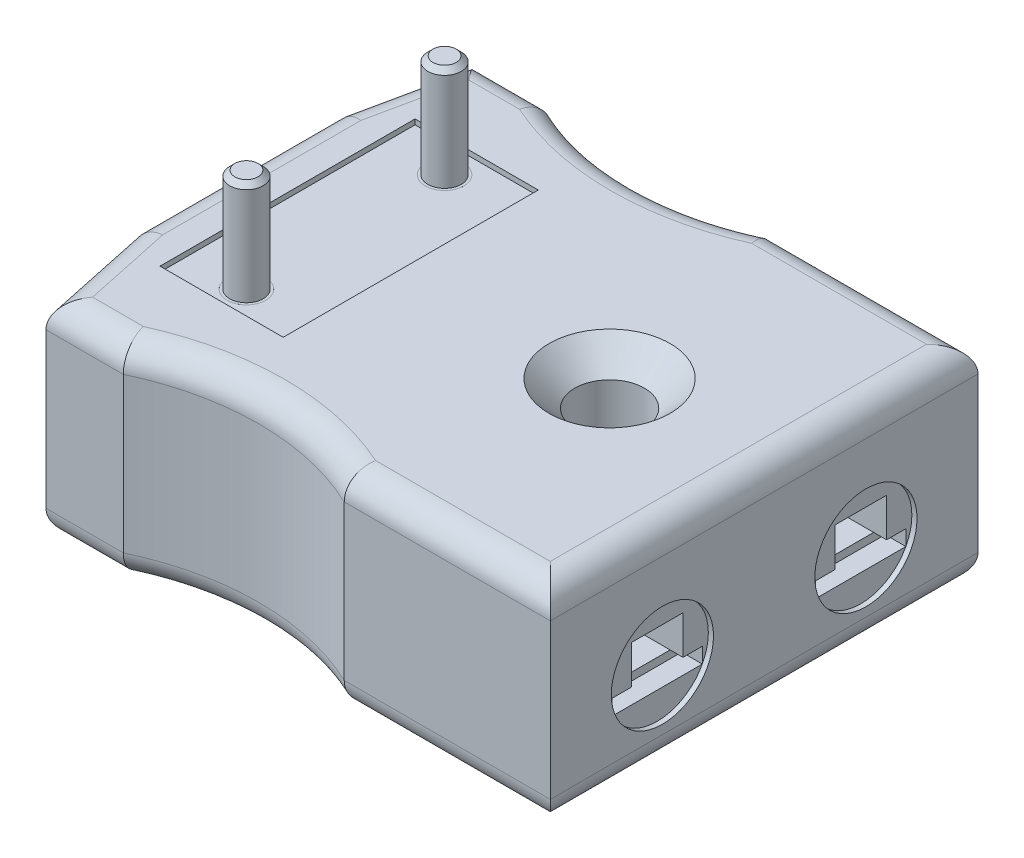
SolidWorks part; units mm, degrees
ref_plane "Front Plane" through (0, 0, 0) normal (0, 0, 1) x (1, 0, 0)
ref_plane "Top Plane" through (0, 0, 0) normal (0, 1, 0) x (1, 0, 0)
ref_plane "Right Plane" through (0, 0, 0) normal (1, 0, 0) x (0, 0, -1)
sketch "Sketch1" plane through (0, 0, 0) normal (0, 1, 0) x (1, 0, 0)
  line L0 (0, -3.95) -> (0, 3.95)
  line L1 (0, 0) -> (28.7651, 0) construction
  line L2 (0, 3.95) -> (0.9246, 8.3)
  line L3 (0.9246, 8.3) -> (3.9246, 8.3)
  line L4 (12.5, 8.3) -> (20.5, 8.3)
  line L5 (20.5, 8.3) -> (20.5, -8.3)
  line L6 (12.5, -8.3) -> (20.5, -8.3)
  line L7 (0.9246, -8.3) -> (3.9246, -8.3)
  line L8 (0, -3.95) -> (0.9246, -8.3)
  arc A0 (3.9246, 8.3) -> (12.5, 8.3) centre (8.2123, 17.3341) ccw
  arc A1 (3.9246, -8.3) -> (12.5, -8.3) centre (8.2123, -17.3341) cw
  point P4 (0, 0)
  point P13 (20.5, 0)
  dimension "D4" = 10
  dimension "D1" = 7.9
  dimension "D2" = 20.5
  dimension "D3" = 16.6
  dimension "D5" = 8
  dimension "D6" = 102
  dimension "D7" = 3
extrude "Boss-Extrude1" add sketch "Sketch1" along normal blind 8
fillet "Fillet1" radius 1 20 edges at (0, 0, 0) (0.4623, 0, 6.125) (2.4246, 0, 8.3) (8.2123, 0, 7.3341) (16.5, 0, 8.3) (20.5, 0, 0) (16.5, 0, -8.3) (8.2123, 0, -7.3341) (2.4246, 0, -8.3) (0.4623, 0, -6.125) (2.4246, 8, -8.3) (8.2123, 8, -7.3341) (16.5, 8, -8.3) (20.5, 8, 0) (16.5, 8, 8.3) (8.2123, 8, 7.3341) (2.4246, 8, 8.3) (0.4623, 8, 6.125) (0, 8, 0) (0.4623, 8, -6.125)
sketch "Sketch2" plane through (0, 8, 0) normal (0, 1, 0) x (1, 0, 0)
  line L0 (20.5, 8.3) -> (20.5, -8.3) construction
  circle A1 centre (14.5, 0) radius 1.35
  dimension "D2" = 2.7
  dimension "D1" = 6
extrude "Cut-Extrude1" cut sketch "Sketch2" against normal through all
chamfer "Chamfer1" distance 1 angle 45 2 edges at (14.5, 0, 1.35) (14.5, 8, 1.35)
sketch "Sketch3" plane through (20.5, 0, 0) normal (-1, 0, 0) x (0, 0, 1)
  line L0 (-4.95, 4.5) -> (-2.95, 4.5)
  line L1 (-2.95, 4.5) -> (-2.95, 3)
  line L2 (-2.95, 3) -> (-2.2, 3)
  line L3 (-2.2, 3) -> (-2.2, 2.4)
  line L4 (-2.2, 2.4) -> (-5.7, 2.4)
  line L5 (-5.7, 2.4) -> (-5.7, 3)
  line L6 (-5.7, 3) -> (-4.95, 3)
  line L7 (-4.95, 3) -> (-4.95, 4.5)
  line L8 (0, 0) -> (0, 9.9505) construction
  line L9 (-3.95, 7) -> (-3.95, 1) construction
  line L10 (3.95, 7) -> (-3.95, 7) construction
  line L11 (4.95, 3) -> (4.95, 4.5)
  line L12 (5.7, 3) -> (4.95, 3)
  line L13 (5.7, 2.4) -> (5.7, 3)
  line L14 (2.2, 2.4) -> (5.7, 2.4)
  line L15 (2.2, 3) -> (2.2, 2.4)
  line L16 (2.95, 3) -> (2.2, 3)
  line L17 (2.95, 4.5) -> (2.95, 3)
  line L18 (4.95, 4.5) -> (2.95, 4.5)
  point P11 (-3.95, 4.5)
  dimension "D1" = 2
  dimension "D2" = 1.5
  dimension "D3" = 0.6
  dimension "D4" = 2.5
  dimension "D5" = 3.5
extrude "Cut-Extrude2" cut sketch "Sketch3" along normal blind 5
sketch "Sketch4" plane through (15.5, 0, 0) normal (1, 0, 0) x (0, 0, -1)
  line L1 (-2.2, 3) -> (-2.2, 2.4) construction
  line L2 (-5.7, 2.4) -> (-2.2, 2.4)
  line L3 (-5.7, 2.4) -> (-5.7, 2.7)
  line L4 (-5.7, 2.7) -> (-2.2, 2.7)
  line L6 (-2.2, 2.4) -> (-2.2, 2.7)
  line L7 (5.7, 3) -> (5.7, 2.4) construction
  line L8 (2.2, 2.4) -> (5.7, 2.4)
  line L9 (2.2, 2.4) -> (2.2, 2.7)
  line L10 (2.2, 2.7) -> (5.7, 2.7)
  line L11 (5.7, 2.4) -> (5.7, 2.7)
extrude "Boss-Extrude2" add sketch "Sketch4" along normal blind 4 separate body
sketch "Sketch5" plane through (0, 0, 0) normal (0, -1, 0) x (1, 0, 0)
  line L0 (0, 0) -> (5.599, 0) construction
  line L1 (2.75, 5.3449) -> (5.75, 5.3449)
  line L2 (2.75, 5.3449) -> (2.75, 4.5949)
  line L3 (2.75, 2.3449) -> (5.75, 2.3449)
  line L4 (5.75, 5.3449) -> (5.75, 2.3449)
  line L5 (2.75, 5.3449) -> (5.75, 2.3449) construction
  line L6 (2.75, 2.3449) -> (5.75, 5.3449) construction
  line L7 (-1.4662, -4.5949) -> (2.75, -4.5949)
  line L8 (2.75, -4.5949) -> (2.75, -5.3449)
  line L9 (2.75, 4.5949) -> (-1.4662, 4.5949)
  line L10 (2.75, -2.3449) -> (5.75, -5.3449) construction
  line L11 (2.75, -5.3449) -> (5.75, -2.3449) construction
  line L12 (5.75, -5.3449) -> (5.75, -2.3449)
  line L13 (2.75, -2.3449) -> (5.75, -2.3449)
  line L14 (2.75, -5.3449) -> (5.75, -5.3449)
  line L15 (20.5, 8.3) -> (20.5, -8.3) construction
  line L16 (-1.4662, 4.5949) -> (-1.4662, 3.0949)
  line L17 (-1.4662, 3.0949) -> (2.75, 3.0949)
  line L18 (2.75, 3.0949) -> (2.75, 2.3449)
  line L20 (-1.4662, -4.5949) -> (-1.4662, -3.0949)
  line L21 (-1.4662, -3.0949) -> (2.75, -3.0949)
  line L22 (2.75, -3.0949) -> (2.75, -2.3449)
  point P0 (4.25, 3.8449)
  point P17 (4.25, -3.8449)
  dimension "D1" = 3
  dimension "D2" = 16.25
  dimension "D3" = 1.5
  dimension "D4" = 3
extrude "Cut-Extrude3" cut sketch "Sketch5" against normal up to surface (2.4 mm away) up to face at (18, 2.4, 3.95)
sketch "Sketch6" plane through (0, 2.4, 0) normal (0, -1, 0) x (1, 0, 0)
  line L0 (2.75, 2.3449) -> (5.75, 2.3449) construction
  line L1 (5.75, 2.3449) -> (5.75, 5.3449) construction
  circle A0 centre (4.25, 3.8449) radius 1
  point P4 (4.25, 2.3449)
  point P7 (5.75, 3.8449)
extrude "Boss-Extrude3" add sketch "Sketch6" along normal blind 1.5 separate body
chamfer "Chamfer2" distance 0.2 angle 45 1 edges at (4.25, 0.9, 2.8449)
sketch "Sketch7" plane through (0, 0.9, 0) normal (0, -1, 0) x (1, 0, 0)
  line L1 (4.1, 3.0591) -> (4.4, 3.0591)
  line L2 (4.1, 3.0591) -> (4.1, 3.6949)
  line L3 (4.1, 4.6307) -> (4.4, 4.6307)
  line L4 (4.4, 3.0591) -> (4.4, 3.6949)
  line L7 (3.4642, 3.6949) -> (4.1, 3.6949)
  line L8 (3.4642, 3.6949) -> (3.4642, 3.9949)
  line L9 (3.4642, 3.9949) -> (4.1, 3.9949)
  line L10 (5.0358, 3.6949) -> (5.0358, 3.9949)
  line L13 (4.1, 3.9949) -> (4.1, 4.6307)
  line L16 (4.4, 3.6949) -> (5.0358, 3.6949)
  line L18 (4.4, 3.9949) -> (4.4, 4.6307)
  line L19 (4.4, 3.9949) -> (5.0358, 3.9949)
  line L20 (3.5028, 4.0095) -> (4.4, 4.6307) construction
  circle A0 centre (4.25, 3.8449) radius 0.8 construction
  point P0 (4.25, 3.8449)
  point P8 (3.5, 3.95)
  dimension "D1" = 0.3
extrude "Cut-Extrude4" cut sketch "Sketch7" against normal blind 1.5 draft 5
fillet "Fillet2" radius 0.2 4 edges at (4.3344, 1.65, 3.9293) (4.3344, 1.65, 3.7605) (4.1656, 1.65, 3.7605) (4.1656, 1.65, 3.9293)
mirror "Mirror1" about plane through (0, 0, 0) normal (0, 0, 1) of bodies 108
sketch "Sketch8" plane through (20.5, 0, 0) normal (-1, 0, 0) x (0, 0, 1)
  line L0 (0, 0) -> (0, 9.6072) construction
  circle A0 centre (3.95, 3.3335) radius 1.9834
  circle A1 centre (-3.95, 3.3335) radius 1.9834
extrude "Cut-Extrude5" cut sketch "Sketch8" along normal blind 0.2
sketch "Sketch9" plane through (0, 0, 0) normal (0, -1, 0) x (1, 0, 0)
  line L0 (19.5, 0) -> (7.4624, 0) construction
  line L1 (19.5, -7.3) -> (19.5, 7.3) construction
  circle A0 centre (17.5191, -3.95) radius 1.5
  circle A1 centre (17.5191, 3.95) radius 1.5
  dimension "D1" = 3
extrude "Cut-Extrude6" cut sketch "Sketch9" against normal blind 0.3
sketch "Sketch10" plane through (0, 0.3, 0) normal (0, -1, 0) x (1, 0, 0)
  line L0 (17.3546, 3.8537) -> (15.9216, 3.8537)
  line L1 (17.6546, 2.2868) -> (17.3546, 2.2868)
  line L2 (17.6546, 2.2868) -> (17.6546, 3.8537)
  line L3 (17.6546, 5.5955) -> (17.3546, 5.5955)
  line L4 (17.3546, 2.2868) -> (17.3546, 3.8537)
  line L5 (19.1575, 3.8537) -> (17.6546, 3.8537)
  line L6 (19.1575, 3.8537) -> (19.1575, 4.1537)
  line L7 (19.1575, 4.1537) -> (17.6546, 4.1537)
  line L8 (15.9216, 3.8537) -> (15.9216, 4.1537)
  line L9 (17.6546, 4.1537) -> (17.6546, 5.5955)
  line L10 (17.3546, 4.1537) -> (15.9216, 4.1537)
  line L11 (17.3546, 4.1537) -> (17.3546, 5.5955)
  dimension "D1" = 0.3
extrude "Boss-Extrude5" add sketch "Sketch10" along normal blind 0.3
sketch "Sketch11" plane through (0, 8, 0) normal (0, 1, 0) x (1, 0, 0)
  line L1 (2, 4.95) -> (6.7814, 4.95)
  line L2 (2, 4.95) -> (2, -4.95)
  line L3 (2, -4.95) -> (6.7814, -4.95)
  line L4 (6.7814, 4.95) -> (6.7814, -4.95)
  point P4 (2, 0)
extrude "Cut-Extrude7" cut sketch "Sketch11" against normal blind 0.2
sketch "Sketch12" plane through (0, 7.8, 0) normal (0, 1, 0) x (1, 0, 0)
  circle A0 centre (4.25, 3.8449) radius 0.75
  circle A1 centre (4.25, -3.8449) radius 0.75
  circle A2 centre (4.25, 3.8449) radius 1 construction
  circle A3 centre (4.25, -3.8449) radius 1 construction
  dimension "D1" = 1.5
extrude "Cut-Extrude8" cut sketch "Sketch12" against normal up to surface (5.4 mm away) up to face at (2.5152, 2.4, -3.8566)
sketch "Sketch13" plane through (0, 2.4, 0) normal (0, 1, 0) x (1, 0, 0)
  circle A0 centre (4.25, 3.8449) radius 0.75 construction
  circle A1 centre (4.25, 3.8449) radius 0.75
  circle A2 centre (4.25, -3.8449) radius 0.75 construction
  circle A3 centre (4.25, -3.8449) radius 0.75
extrude "Boss-Extrude6" add sketch "Sketch13" along normal up to surface (5.4 mm away) up to face at (4.25, 7.8, 4.5949)
sketch "Sketch14" plane through (0, 7.8, 0) normal (0, 1, 0) x (1, 0, 0)
  circle A0 centre (4.25, -3.8449) radius 0.65
  circle A1 centre (4.25, 3.8449) radius 0.65
  dimension "D1" = 1.3
extrude "Boss-Extrude7" add sketch "Sketch14" along normal blind 4
chamfer "Chamfer3" distance 0.2 angle 45 1 edges at (4.25, 11.8, 4.4949)
chamfer "Chamfer4" distance 0.2 angle 45 1 edges at (4.25, 11.8, -3.1949)
sketch "Sketch15" plane through (0, 0.3, 0) normal (0, -1, 0) x (1, 0, 0)
  line L0 (18.6653, -3.2341) -> (18.6653, -6.3102) construction
  text T0 "k" font "Century Gothic" height 2
extrude "Boss-Extrude8" add sketch "Sketch15" along normal up to surface (0.3 mm away) up to face at (18.1945, 0, 3.304)
